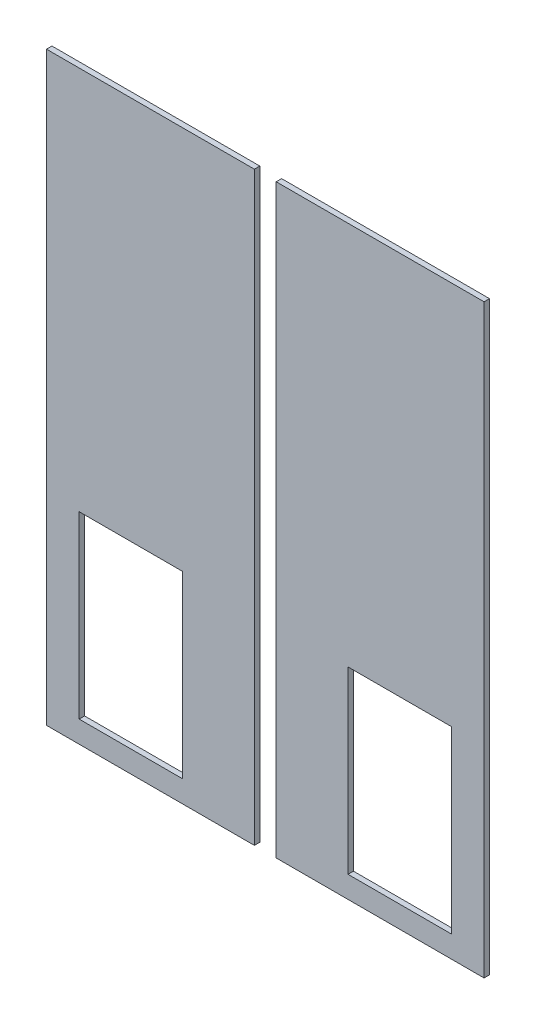
SolidWorks part; units mm, degrees
material "PE High Density Film"
ref_plane "Front Plane" through (0, 0, 0) normal (0, 0, 1) x (1, 0, 0)
ref_plane "Top Plane" through (0, 0, 0) normal (0, 1, 0) x (1, 0, 0)
ref_plane "Right Plane" through (0, 0, 0) normal (1, 0, 0) x (0, 0, -1)
sketch "Sketch1" plane through (0, 0, 0) normal (0, 0, 1) x (1, 0, 0)
  line L0 (-242.57, 341.63) -> (-242.57, -341.63) construction
  line L1 (-255.27, 341.63) -> (255.27, 341.63)
  line L2 (-255.27, 341.63) -> (-255.27, -341.63)
  line L3 (-255.27, -341.63) -> (255.27, -341.63)
  line L4 (255.27, 341.63) -> (255.27, -341.63)
  line L5 (-255.27, 341.63) -> (255.27, -341.63) construction
  line L6 (-255.27, -341.63) -> (255.27, 341.63) construction
  line L7 (-217.17, 341.63) -> (-217.17, -341.63) construction
  line L8 (-255.27, -316.23) -> (255.27, -316.23) construction
  line L9 (-217.17, -106.68) -> (-96.52, -106.68)
  line L10 (-217.17, -316.23) -> (-102.87, -316.23) construction
  line L11 (-217.17, -316.23) -> (-217.17, -113.03) construction
  line L12 (-217.17, -113.03) -> (-102.87, -113.03) construction
  line L13 (-102.87, -316.23) -> (-102.87, -113.03) construction
  line L14 (-96.52, -316.23) -> (-96.52, -106.68)
  line L15 (-217.17, -106.68) -> (-217.17, -316.23)
  line L16 (-217.17, -316.23) -> (-96.52, -316.23)
  line L17 (0, 341.63) -> (0, -341.63) construction
  line L18 (217.17, -316.23) -> (96.52, -316.23)
  line L19 (96.52, -316.23) -> (96.52, -106.68)
  line L20 (217.17, -106.68) -> (217.17, -316.23)
  line L21 (217.17, -106.68) -> (96.52, -106.68)
  line L22 (-12.7, 341.63) -> (-12.7, -341.63)
  line L23 (12.7, 341.63) -> (12.7, -341.63)
  point P0 (0, 0)
  dimension "D1" = 510.54
  dimension "D2" = 683.26
  dimension "D3" = 12.7
  dimension "D5" = 25.4
  dimension "D6" = 114.3
  dimension "D7" = 203.2
  dimension "D4" = 25.4
  dimension "D8" = 6.35
  dimension "D9" = 12.7
  dimension "D10" = 12.7
extrude "Boss-Extrude1" add sketch "Sketch1" along normal blind 6.35 contours L22 L1 L2 L3 L16 L15 L9 L14 | L1 L23 L3 L4 L21 L20 L18 L19
